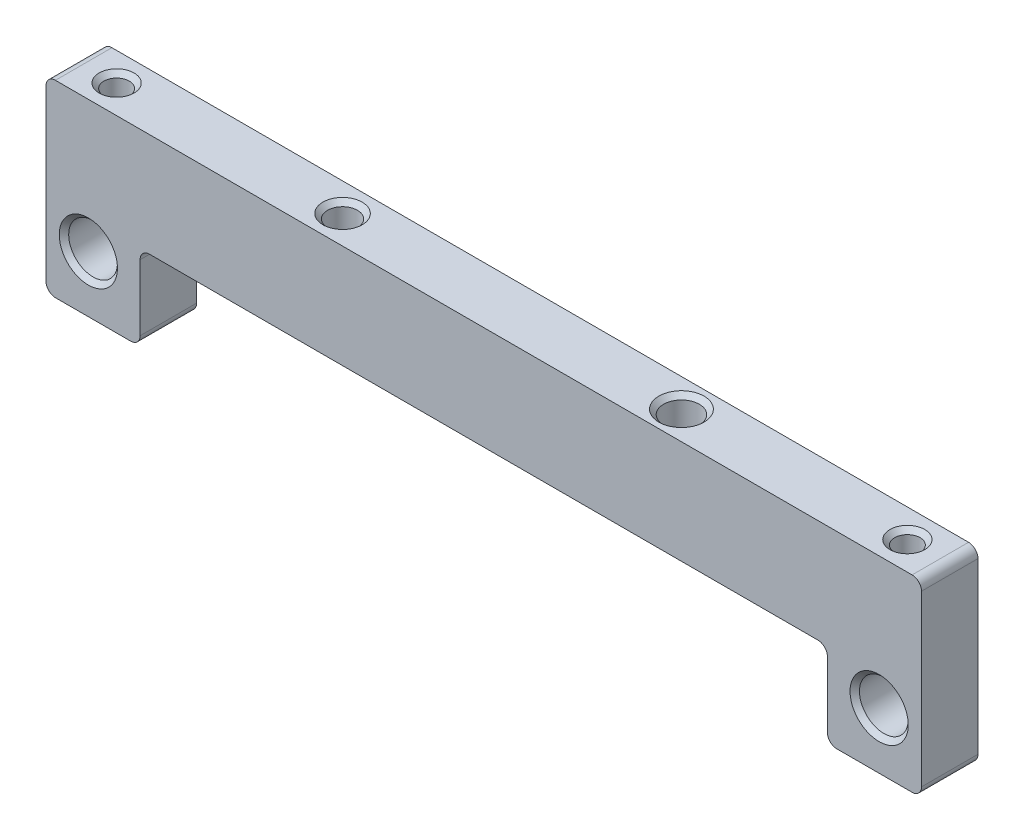
SolidWorks part; units mm, degrees
material "6063-T6"
ref_plane "Front" through (0, 0, 0) normal (0, 0, 1) x (1, 0, 0)
ref_plane "Top" through (0, 0, 0) normal (0, 1, 0) x (1, 0, 0)
ref_plane "Right" through (0, 0, 0) normal (1, 0, 0) x (0, 0, -1)
sketch "Sketch1" plane through (0, 0, 0) normal (0, 0, 1) x (1, 0, 0)
  line L1 (-46.5, -10) -> (46.5, -10)
  line L2 (-46.5, -10) -> (-46.5, 10)
  line L3 (-46.5, 10) -> (46.5, 10)
  line L4 (46.5, -10) -> (46.5, 10)
  line L5 (-46.5, -10) -> (46.5, 10) construction
  line L6 (-46.5, 10) -> (46.5, -10) construction
  point P0 (0, 0)
  dimension "D1" = 20
  dimension "D2" = 93
extrude "Boss-Extrude1" add sketch "Sketch1" along normal blind 6
sketch "Sketch2" plane through (0, 0, 6) normal (0, 0, 1) x (1, 0, 0)
  line L0 (-46.5, -10) -> (46.5, -10) construction
  line L1 (-36.5, -10) -> (36.5, -10)
  line L2 (-36.5, -10) -> (-36.5, -1)
  line L3 (-36.5, -1) -> (36.5, -1)
  line L4 (36.5, -10) -> (36.5, -1)
  line L5 (0, 0) -> (0, 50000) construction
  dimension "D1" = 9
  dimension "D2" = 73
extrude "Cut-Extrude1" cut sketch "Sketch2" against normal up to next
hole_wizard "#6 (0.204) Diameter Hole1" positions "Sketch6" profile "Sketch5" hole size "#6" standard "ANSI Inch" end condition up to next
sketch "Sketch6" plane through (0, 0, 6) normal (0, 0, 1) x (1, 0, 0)
  line L0 (0, 0) -> (0, 50000) construction
  line L1 (-46.5, -10) -> (-36.5, -10) construction
  point P4 (-42, -4)
  point P8 (42, -4)
  dimension "D1" = 6
  dimension "D2" = 84
sketch "Sketch5" plane through (42, -4, 6) normal (1, 0, 0) x (0, -1, 0)
  line L0 (0, 0) -> (0, 6)
  line L1 (0, 6) -> (2.5908, 6)
  line L2 (2.5908, 6) -> (2.5908, 0)
  line L5 (2.5908, 0) -> (0, 0)
  line L11 (0, -6.35) -> (0, 107.95) construction
  dimension "Thru Hole Dia." = 5.1816
  dimension "Thru Hole Depth" = 6
hole_wizard "#6 Clearance Hole1" positions "Sketch7" profile "Sketch8" hole size "#6" standard "ANSI Inch" end condition up to next
sketch "Sketch7" plane through (0, 10, 0) normal (0, 1, 0) x (1, 0, 0)
  line L0 (0, 0) -> (0, 50000) construction
  line L1 (-46.5, -3) -> (49953.5, -3) construction
  line L2 (-46.5, -6) -> (-46.5, 0) construction
  point P11 (-46.5, -3)
  point P15 (18, -3)
  dimension "D1" = 18
sketch "Sketch8" plane through (18, 10, 3) normal (1, 0, 0) x (0, 0, 1)
  line L0 (0, 0) -> (0, 11)
  line L1 (0, 11) -> (1.8986, 11)
  line L2 (1.8986, 11) -> (1.8986, 0)
  line L5 (1.8986, 0) -> (0, 0)
  line L11 (0, -6.35) -> (0, 107.95) construction
  dimension "Thru Hole Dia." = 3.7973
  dimension "Thru Hole Depth" = 11
hole_wizard "#6-32 Tapped Hole1" positions "Sketch9" profile "Sketch10" tap size "#6-32" standard "ANSI Inch"
sketch "Sketch9" plane through (0, 10, 0) normal (0, 1, 0) x (1, 0, 0)
  line L0 (0, 0) -> (0, 50000) construction
  line L1 (-46.5, -3) -> (49953.5, -3) construction
  line L2 (-46.5, -6) -> (-46.5, 0) construction
  point P0 (-42, -3)
  point P11 (-46.5, -3)
  point P15 (42, -3)
  dimension "D1" = 84
sketch "Sketch10" plane through (-42, 10, 3) normal (1, 0, 0) x (0, 0, 1)
  line L0 (0, 0) -> (0, 11.4092)
  line L1 (0, 11.4092) -> (1.3525, 11.4092)
  line L2 (1.3525, 11.4092) -> (1.3525, 0)
  line L5 (1.3525, 0) -> (0, 0)
  line L11 (0, -6.35) -> (0, 107.95) construction
  dimension "Thread Major Dia." = 2.7051
  dimension "Thru Tap Drill Depth" = 11.4092
hole_wizard "1/8 (0.125) Diameter Hole1" positions "Sketch11" profile "Sketch12" hole size "1/8" standard "ANSI Inch" end condition up to next
sketch "Sketch11" plane through (0, 10, 0) normal (0, 1, 0) x (1, 0, 0)
  line L0 (46.5, 0) -> (-46.5, 0) construction
  circle A0 centre (18, -3) radius 1.8986 construction
  circle A1 centre (18, -3) radius 1.8986 construction
  point P0 (-18, -3)
  point P3 (0, 0)
  point P7 (0, 0)
  point P10 (0, 0)
  dimension "D1" = 18
sketch "Sketch12" plane through (-18, 10, 3) normal (1, 0, 0) x (0, 0, 1)
  line L0 (0, 0) -> (0, 11)
  line L1 (0, 11) -> (1.5875, 11)
  line L2 (1.5875, 11) -> (1.5875, 0)
  line L5 (1.5875, 0) -> (0, 0)
  line L11 (0, -6.35) -> (0, 107.95) construction
  dimension "Thru Hole Dia." = 3.175
  dimension "Thru Hole Depth" = 11
fillet "Fillet1" radius 1 8 edges at (36.5, -1, 3) (36.5, -10, 3) (46.5, -10, 3) (46.5, 10, 3) (-46.5, 10, 3) (-46.5, -10, 3) (-36.5, -10, 3) (-36.5, -1, 3)
chamfer "Chamfer1" distance 0.5 angle 45 10 edges at (39.4092, -4, 0) (44.5908, -4, 6) (-44.5908, -4, 0) (-39.4092, -4, 6) (18, -1, 4.8986) (-18, -1, 4.5875) (42, 10, 4.3525) (-42, 10, 4.3525) (18, 10, 4.8986) (-18, 10, 4.5875)
